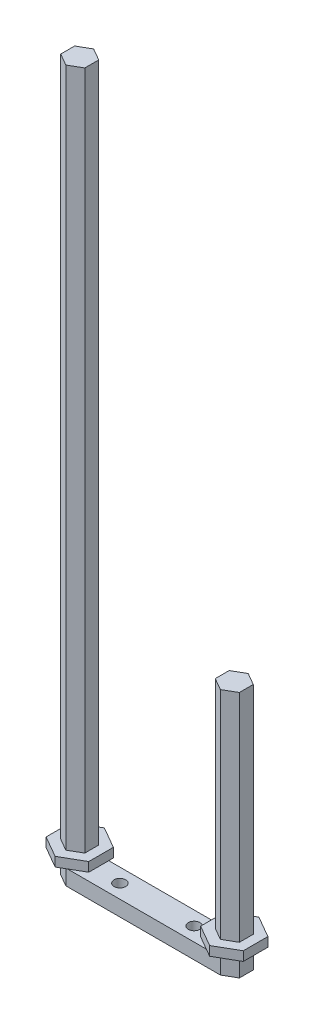
SolidWorks part; units mm, degrees
ref_plane "Front Plane" through (0, 0, 0) normal (0, 0, 1) x (1, 0, 0)
ref_plane "Top Plane" through (0, 0, 0) normal (0, 1, 0) x (1, 0, 0)
ref_plane "Right Plane" through (0, 0, 0) normal (1, 0, 0) x (0, 0, -1)
sketch "Sketch1" plane through (0, 0, 0) normal (0, 1, 0) x (1, 0, 0)
  line L0 (0, 0) -> (24, 0) construction
  line L1 (12, 0) -> (12, 8.3849) construction
  line L2 (-13, 4.5) -> (37, 4.5)
  line L3 (-13, 4.5) -> (-13, -4.5)
  line L4 (-13, -4.5) -> (37, -4.5)
  line L5 (37, 4.5) -> (37, -4.5)
  circle A0 centre (24, 0) radius 1.9
  circle A1 centre (0, 0) radius 1.9
  dimension "D1" = 3.8
  dimension "D2" = 24
  dimension "D3" = 9
  dimension "D4" = 50
extrude "Boss-Extrude1" add sketch "Sketch1" along normal blind 5
sketch "Sketch3" plane through (0, 0, 0) normal (0, -1, 0) x (1, 0, 0)
  line L1 (-13, -4.5) -> (-13, 4.5) construction
  line L2 (-13, 4.5) -> (-16.8971, 2.25)
  line L4 (-16.8971, 2.25) -> (-16.8971, -2.25)
  line L5 (-16.8971, -2.25) -> (-13, -4.5)
  line L6 (-13, -4.5) -> (-9.1029, -2.25)
  line L7 (-9.1029, -2.25) -> (-9.1029, 2.25)
  line L8 (-9.1029, 2.25) -> (-13, 4.5)
  line L10 (37, -4.5) -> (-13, -4.5) construction
  line L11 (12, -4.5) -> (12, 4.5) construction
  line L14 (-13, 4.5) -> (37, 4.5) construction
  line L15 (33.1029, 2.25) -> (37, 4.5)
  line L16 (33.1029, -2.25) -> (33.1029, 2.25)
  line L17 (37, -4.5) -> (33.1029, -2.25)
  line L18 (40.8971, -2.25) -> (37, -4.5)
  line L19 (40.8971, 2.25) -> (40.8971, -2.25)
  line L20 (37, 4.5) -> (40.8971, 2.25)
  circle A0 centre (37, 0) radius 3.8971 construction
  circle A1 centre (-13, 0) radius 3.8971 construction
extrude "Boss-Extrude2" add sketch "Sketch3" against normal blind 80
sketch "Sketch4" plane through (0, 80, 0) normal (0, 1, 0) x (1, 0, 0)
  line L6 (-13, -4.5) -> (-9.1029, -2.25)
  line L7 (-9.1029, -2.25) -> (-9.1029, 2.25)
  line L8 (-9.1029, 2.25) -> (-13, 4.5)
  line L9 (-13, 4.5) -> (-16.8971, 2.25)
  line L10 (-16.8971, 2.25) -> (-16.8971, -2.25)
  line L11 (-16.8971, -2.25) -> (-13, -4.5)
  line L12 (-13, -4.5) -> (-9.1029, -2.25)
  line L13 (-9.1029, -2.25) -> (-9.1029, 2.25)
  line L14 (-9.1029, 2.25) -> (-13, 4.5)
  line L15 (-13, 4.5) -> (-16.8971, 2.25)
  line L16 (-16.8971, 2.25) -> (-16.8971, -2.25)
  line L17 (-16.8971, -2.25) -> (-13, -4.5)
  dimension "D1" = 0
extrude "Boss-Extrude3" add sketch "Sketch4" along normal blind 150
ref_plane "Plane1" through (0, 7, 0) normal (0, -1, 0) x (-1, 0, 0)
sketch "Sketch5" plane through (0, 7, 0) normal (0, -1, 0) x (-1, 0, 0)
  line L0 (16.8971, -2.25) -> (13, -4.5) construction
  line L1 (13, -4.5) -> (9.1029, -2.25) construction
  line L2 (9.1029, -2.25) -> (9.1029, 2.25) construction
  line L3 (9.1029, 2.25) -> (13, 4.5) construction
  line L4 (13, 4.5) -> (16.8971, 2.25) construction
  line L5 (16.8971, 2.25) -> (16.8971, -2.25) construction
  line L7 (-33.1029, -2.25) -> (-37, -4.5) construction
  line L8 (-37, -4.5) -> (-40.8971, -2.25) construction
  line L10 (-40.8971, 2.25) -> (-37, 4.5) construction
  line L11 (-37, 4.5) -> (-33.1029, 2.25) construction
  line L12 (16.8971, -2.25) -> (13, -4.5)
  line L13 (13, -4.5) -> (9.1029, -2.25)
  line L14 (9.1029, -2.25) -> (9.1029, 2.25)
  line L15 (9.1029, 2.25) -> (13, 4.5)
  line L16 (13, 4.5) -> (16.8971, 2.25)
  line L17 (16.8971, 2.25) -> (16.8971, -2.25)
  line L18 (-33.1029, 2.25) -> (-33.1029, -2.25)
  line L19 (-33.1029, -2.25) -> (-37, -4.5)
  line L20 (-37, -4.5) -> (-40.8971, -2.25)
  line L21 (-40.8971, -2.25) -> (-40.8971, 2.25)
  line L22 (-40.8971, 2.25) -> (-37, 4.5)
  line L23 (-37, 4.5) -> (-33.1029, 2.25)
  line L24 (19.8971, 3.9821) -> (19.8971, -3.9821)
  line L25 (19.8971, -3.9821) -> (13, -7.9641)
  line L26 (13, -7.9641) -> (6.1029, -3.9821)
  line L27 (6.1029, -3.9821) -> (6.1029, 3.9821)
  line L28 (6.1029, 3.9821) -> (13, 7.9641)
  line L29 (13, 7.9641) -> (19.8971, 3.9821)
  line L30 (-43.8971, -3.9821) -> (-43.8971, 3.9821)
  line L31 (-43.8971, 3.9821) -> (-37, 7.9641)
  line L32 (-37, 7.9641) -> (-30.1029, 3.9821)
  line L33 (-30.1029, 3.9821) -> (-30.1029, -3.9821)
  line L34 (-30.1029, -3.9821) -> (-37, -7.9641)
  line L35 (-37, -7.9641) -> (-43.8971, -3.9821)
  dimension "D1" = 3
extrude "Boss-Extrude4" add sketch "Sketch5" against normal blind 3
